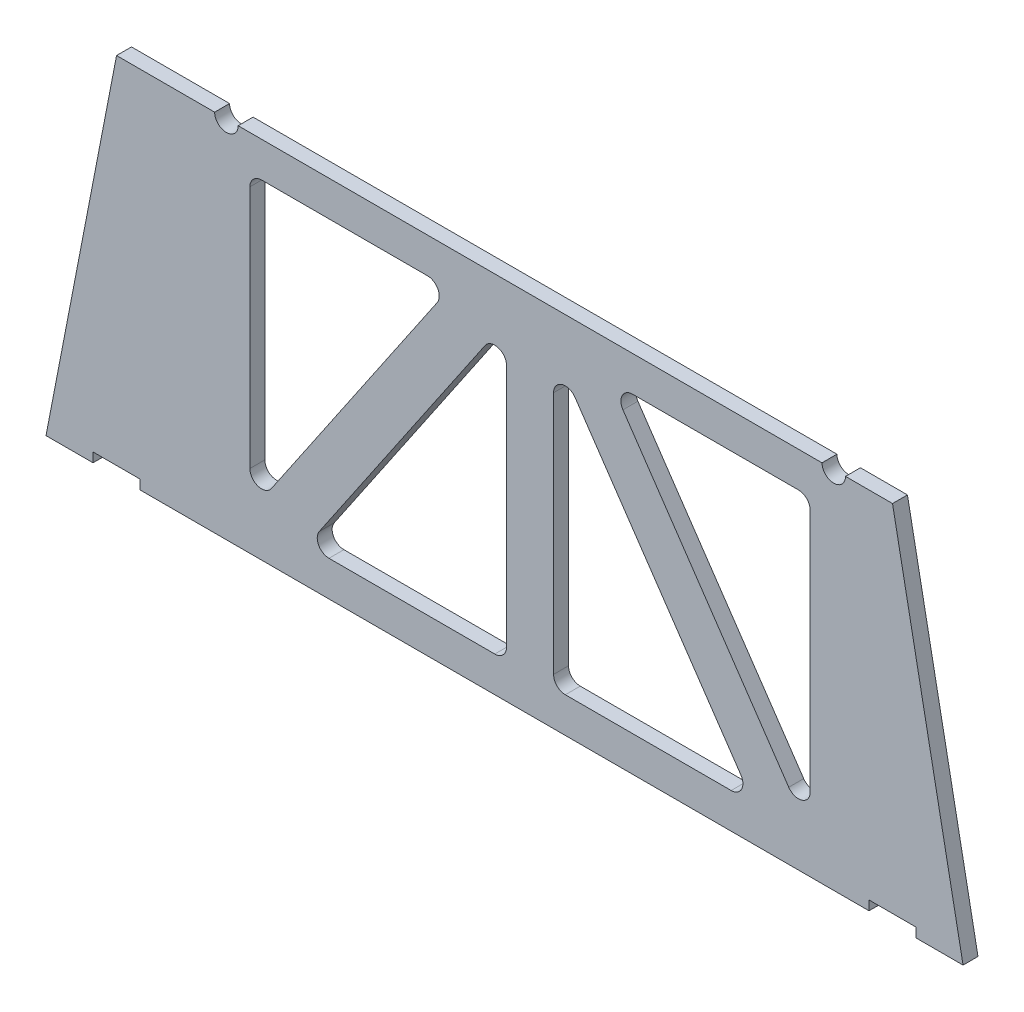
SolidWorks part; units mm, degrees
ref_plane "Front Plane" through (0, 0, 0) normal (0, 0, 1) x (1, 0, 0)
ref_plane "Top Plane" through (0, 0, 0) normal (0, 1, 0) x (1, 0, 0)
ref_plane "Right Plane" through (0, 0, 0) normal (1, 0, 0) x (0, 0, -1)
sketch "Sketch1" plane through (0, 0, 0) normal (0, 0, 1) x (1, 0, 0)
  line L0 (-165.8562, -77.5) -> (144.1438, -77.5)
  line L1 (184.1438, -77.5) -> (154.1437, 77.5)
  line L2 (154.1437, 77.5) -> (134.1438, 77.5)
  line L3 (-175.8562, 77.5) -> (-205.8562, -77.5)
  line L4 (-205.8562, -77.5) -> (-185.8562, -77.5)
  line L5 (-185.8562, -77.5) -> (-185.8562, -73.5)
  line L6 (-185.8562, -73.5) -> (-165.8562, -73.5)
  line L7 (-165.8562, -73.5) -> (-165.8562, -77.5)
  line L8 (-175.8562, 77.5) -> (-134.1438, 77.5)
  line L9 (144.1438, -77.5) -> (144.1438, -73.5)
  line L10 (144.1438, -73.5) -> (164.1438, -73.5)
  line L11 (164.1438, -73.5) -> (164.1438, -77.5)
  line L12 (164.1438, -77.5) -> (184.1438, -77.5)
  line L13 (-175.8562, 77.5) -> (-134.1438, 77.5)
  line L14 (0, -77.5) -> (0, 77.5) construction
  line L15 (-124.1437, 77.5) -> (124.1437, 77.5)
  line L16 (-119.1437, 57.5) -> (-119.1437, -46.249)
  line L17 (-110.0085, -49.0597) -> (-39.4913, 54.6893)
  line L18 (-114.1437, 62.5) -> (-43.6265, 62.5)
  line L19 (-89.6524, -54.6893) -> (-19.1352, 49.0597)
  line L20 (-10, 46.249) -> (-10, -57.5)
  line L21 (-85.5172, -62.5) -> (-15, -62.5)
  line L22 (15, -62.5) -> (85.5172, -62.5)
  line L23 (10, 46.249) -> (10, -57.5)
  line L24 (89.6524, -54.6893) -> (19.1352, 49.0597)
  line L25 (43.6265, 62.5) -> (114.1437, 62.5)
  line L26 (110.0085, -49.0597) -> (39.4913, 54.6893)
  line L27 (119.1437, 57.5) -> (119.1437, -46.249)
  arc A0 (-134.1438, 77.5) -> (-124.1437, 77.5) centre (-129.1438, 77.5) ccw
  arc A1 (134.1438, 77.5) -> (124.1437, 77.5) centre (129.1438, 77.5) cw
  arc A2 (-119.1437, 57.5) -> (-114.1437, 62.5) centre (-114.1437, 57.5) cw
  arc A3 (-110.0085, -49.0597) -> (-119.1437, -46.249) centre (-114.1437, -46.249) cw
  arc A4 (-39.4913, 54.6893) -> (-43.6265, 62.5) centre (-43.6265, 57.5) ccw
  arc A5 (-10, 46.249) -> (-19.1352, 49.0597) centre (-15, 46.249) ccw
  arc A6 (-15, -62.5) -> (-10, -57.5) centre (-15, -57.5) ccw
  arc A7 (-85.5172, -62.5) -> (-89.6524, -54.6893) centre (-85.5172, -57.5) cw
  arc A8 (10, 46.249) -> (19.1352, 49.0597) centre (15, 46.249) cw
  arc A9 (10, -57.5) -> (15, -62.5) centre (15, -57.5) ccw
  arc A10 (85.5172, -62.5) -> (89.6524, -54.6893) centre (85.5172, -57.5) ccw
  arc A11 (43.6265, 62.5) -> (39.4913, 54.6893) centre (43.6265, 57.5) ccw
  arc A12 (119.1437, 57.5) -> (114.1437, 62.5) centre (114.1437, 57.5) ccw
  arc A13 (110.0085, -49.0597) -> (119.1437, -46.249) centre (114.1437, -46.249) ccw
  point P15 (0, -77.5)
  point P29 (0, 0)
  point P37 (-119.1437, 62.5)
  point P40 (-119.1437, -62.5)
  point P43 (-34.1825, 62.5)
  point P46 (-10, 62.5)
  point P49 (-10, -62.5)
  point P52 (-94.9613, -62.5)
  point P55 (10, 62.5)
  point P58 (10, -62.5)
  point P61 (94.9613, -62.5)
  point P64 (34.1825, 62.5)
  point P67 (119.1437, 62.5)
  point P70 (119.1437, -62.5)
  dimension "D18" = 5
  dimension "D1" = 20
  dimension "D2" = 20
  dimension "D3" = 20
  dimension "D4" = 268.2875
  dimension "D5" = 15
  dimension "D6" = 10
  dimension "D7" = 20
  dimension "D8" = 4
  dimension "D9" = 10
  dimension "D10" = 310
  dimension "D11" = 5
  dimension "D13" = 20
  dimension "D14" = 10
  dimension "D15" = 15
  dimension "D16" = 155
  dimension "D17" = 5
extrude "Extrude1" add sketch "Sketch1" along normal blind 6.35 contours L0 L14 L15 A0 L8 L3 L4 L5 L6 L7 L16 L18 L17 L21 L19 L20 | L14 L0 L9 L10 L11 L12 L1 L2 A1 L15 L25 L27 L26 L24 L22 L23
